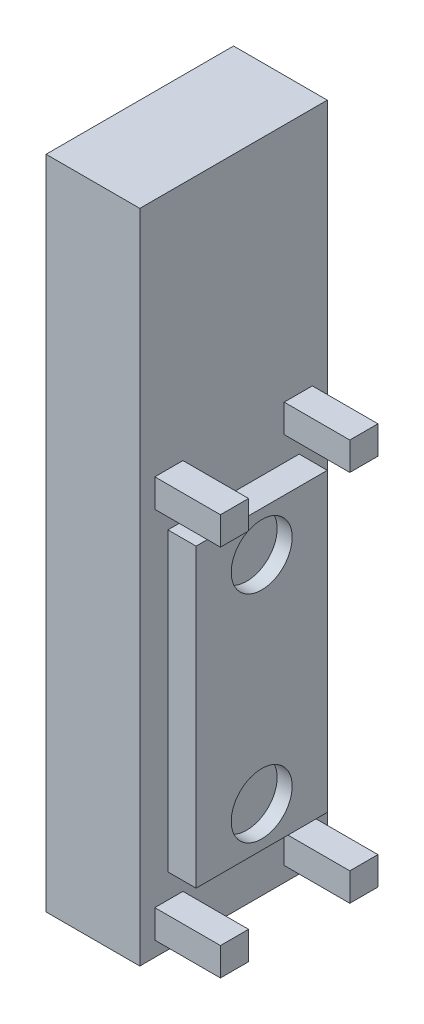
SolidWorks part; units mm, degrees
ref_plane "Front Plane" through (0, 0, 0) normal (0, 0, 1) x (1, 0, 0)
ref_plane "Top Plane" through (0, 0, 0) normal (0, 1, 0) x (1, 0, 0)
ref_plane "Right Plane" through (0, 0, 0) normal (1, 0, 0) x (0, 0, -1)
sketch "Sketch1" plane through (0, 0, 0) normal (1, 0, 0) x (0, 0, -1)
  line L1 (-10, -35) -> (10, -35)
  line L2 (-10, -35) -> (-10, 35)
  line L3 (-10, 35) -> (10, 35)
  line L4 (10, -35) -> (10, 35)
  line L5 (-10, -35) -> (10, 35) construction
  line L6 (-10, 35) -> (10, -35) construction
  point P0 (0, 0)
  dimension "D1" = 70
  dimension "D2" = 20
extrude "Boss-Extrude1" add sketch "Sketch1" along normal blind 10
sketch "Sketch2" plane through (10, 0, 0) normal (1, 0, 0) x (0, 0, -1)
  line L0 (0, 35) -> (0, -35) construction
  line L1 (-10, -12) -> (10, -12) construction
  line L2 (-8.4, 6.4) -> (-5.4, 6.4)
  line L3 (-8.4, 6.4) -> (-8.4, 9.4)
  line L4 (-8.4, 9.4) -> (-5.4, 9.4)
  line L5 (-5.4, 6.4) -> (-5.4, 9.4)
  line L6 (-8.4, 6.4) -> (-5.4, 9.4) construction
  line L7 (-8.4, 9.4) -> (-5.4, 6.4) construction
  line L8 (8.4, 9.4) -> (5.4, 6.4) construction
  line L9 (8.4, 6.4) -> (5.4, 9.4) construction
  line L10 (5.4, 6.4) -> (5.4, 9.4)
  line L11 (8.4, 9.4) -> (5.4, 9.4)
  line L12 (8.4, 6.4) -> (8.4, 9.4)
  line L13 (8.4, 6.4) -> (5.4, 6.4)
  line L14 (8.4, -30.4) -> (5.4, -33.4) construction
  line L15 (8.4, -33.4) -> (5.4, -30.4) construction
  line L16 (-8.4, -33.4) -> (-5.4, -30.4) construction
  line L17 (-8.4, -30.4) -> (-5.4, -33.4) construction
  line L18 (8.4, -30.4) -> (5.4, -30.4)
  line L19 (8.4, -30.4) -> (8.4, -33.4)
  line L20 (8.4, -33.4) -> (5.4, -33.4)
  line L21 (5.4, -30.4) -> (5.4, -33.4)
  line L22 (-5.4, -30.4) -> (-5.4, -33.4)
  line L23 (-8.4, -33.4) -> (-5.4, -33.4)
  line L24 (-8.4, -30.4) -> (-8.4, -33.4)
  line L25 (-8.4, -30.4) -> (-5.4, -30.4)
  line L26 (-10, 35) -> (-10, -35) construction
  line L27 (10, -35) -> (10, 35) construction
  line L28 (-10, -35) -> (10, -35) construction
  line L29 (10, 35) -> (-10, 35) construction
  point P4 (-6.9, 7.9)
  point P13 (6.9, 7.9)
  point P22 (6.9, -31.9)
  point P23 (-6.9, -31.9)
  point P24 (0.2455, -10.984)
  point P25 (-10, -10.984)
  point P28 (10, -10.984)
  point P31 (0, -35)
  point P34 (0, 35)
  dimension "D1" = 3
  dimension "D2" = 3
  dimension "D3" = 1.6
  dimension "D4" = 1.6
  dimension "D5" = 18.4
extrude "Boss-Extrude2" add sketch "Sketch2" along normal blind 7
sketch "Sketch3" plane through (10, 0, 0) normal (1, 0, 0) x (0, 0, -1)
  line L0 (0, 35) -> (0, -35) construction
  line L1 (10, 35) -> (-10, 35) construction
  line L2 (-10, -35) -> (10, -35) construction
  line L3 (-8.4, 6.4) -> (-5.4, 6.4) construction
  line L4 (-7, -27.8) -> (7, -27.8)
  line L5 (-7, -27.8) -> (-7, 3.8)
  line L6 (-7, 3.8) -> (7, 3.8)
  line L7 (7, -27.8) -> (7, 3.8)
  line L8 (-7, -27.8) -> (7, 3.8) construction
  line L9 (-7, 3.8) -> (7, -27.8) construction
  point P6 (0, -12)
  point P11 (0, -11.9147)
  dimension "D1" = 31.6
  dimension "D2" = 14
  dimension "D3" = 2.6
extrude "Boss-Extrude3" add sketch "Sketch3" along normal blind 3
sketch "Sketch4" plane through (13, 0, 0) normal (1, 0, 0) x (0, 0, -1)
  line L0 (-10, -35) -> (10, -35) construction
  line L1 (0, 10.3232) -> (0, -32.276) construction
  circle A0 centre (0, -23.5) radius 3.25
  circle A1 centre (0, -0.5) radius 3.25
  point P9 (0, -0.5)
  dimension "D1" = 6.5
  dimension "D3" = 6.5
  dimension "D2" = 11.5
  dimension "D4" = 23
extrude "Cut-Extrude1" cut sketch "Sketch4" against normal blind 1.6
